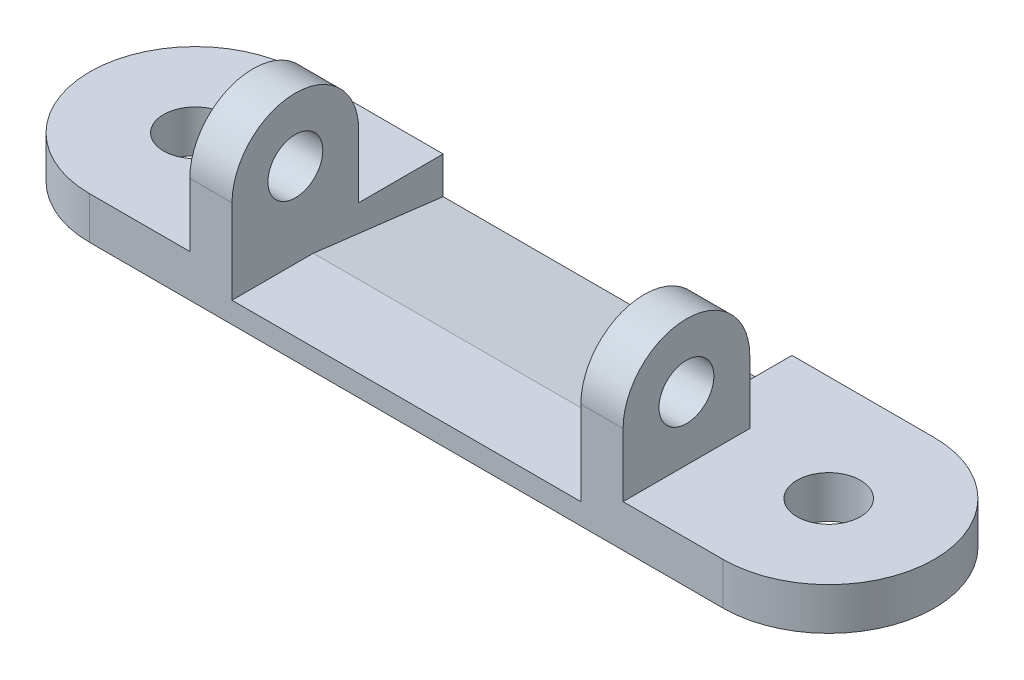
SolidWorks part; units mm, degrees
ref_plane "Front Plane" through (0, 0, 0) normal (0, 0, 1) x (1, 0, 0)
ref_plane "Top Plane" through (0, 0, 0) normal (0, 1, 0) x (1, 0, 0)
ref_plane "Right Plane" through (0, 0, 0) normal (1, 0, 0) x (0, 0, -1)
sketch "Sketch1" plane through (0, 0, 0) normal (0, 1, 0) x (1, 0, 0)
  line L1 (-30, 10) -> (30, 10)
  line L2 (-30, 10) -> (-30, -10) construction
  line L3 (-30, -10) -> (30, -10)
  line L4 (30, 10) -> (30, -10) construction
  line L5 (-30, 10) -> (30, -10) construction
  line L6 (-30, -10) -> (30, 10) construction
  arc A0 (-30, 10) -> (-30, -10) centre (-30, 0) ccw
  arc A1 (30, 10) -> (30, -10) centre (30, 0) cw
  point P0 (0, 0)
  dimension "D1" = 60
  dimension "D2" = 20
extrude "Boss-Extrude1" add sketch "Sketch1" along normal blind 4
sketch "Sketch2" plane through (0, 4, 0) normal (0, 1, 0) x (1, 0, 0)
  circle A0 centre (-30, 0) radius 3
  circle A1 centre (30, 0) radius 3
  arc A2 (-30, 10) -> (-30, -10) centre (-30, 0) ccw construction
  arc A3 (30, -10) -> (30, 10) centre (30, 0) ccw construction
  dimension "D1" = 6
extrude "Cut-Extrude1" cut sketch "Sketch2" against normal through all
sketch3d "3DSketch1"
  line L0 (-16.5227, 4, 10) -> (-16.5227, 4, -2)
  line L1 (-30, 4, 10) -> (30, 4, 10) construction
  line L4 (-16.5227, 4, 10) -> (-16.5227, 10, 10)
  line L5 (-16.5227, 4, -2) -> (-16.5227, 10, -2)
  arc A0 (-16.5227, 10, 10) -> (-16.5227, 10, -2) centre (-16.5227, 10, 4) cw
  point P11 (-22.5227, 10, 4)
  dimension "D1" = 17
  dimension "D2" = 6
  dimension "D3" = 12
extrude "Boss-Extrude2" add sketch "3DSketch1" along direction (1, 0, 0) on the side of the normal blind 4
sketch "Sketch3" plane through (-16.5227, 0, 0) normal (1, 0, 0) x (0, 0, -1)
  circle A0 centre (-4, 10) radius 2.6
  arc A1 (2, 10) -> (-10, 10) centre (-4, 10) ccw construction
  dimension "D1" = 5.2
extrude "Cut-Extrude2" cut sketch "Sketch3" against normal through all
sketch "Sketch4" plane through (0, 0, 0) normal (1, 0, 0) x (0, 0, -1)
  line L0 (-10, 2) -> (-2.3, 2)
  line L1 (-10, 4) -> (-10, 0) construction
  line L2 (-2.3, 2) -> (10, 0.5)
  line L3 (10, 4) -> (10, 0) construction
  line L4 (-10, 2) -> (-10, 0)
  line L5 (-10, 0) -> (10, 0)
  line L6 (10, 0) -> (10, 0.5)
  dimension "D1" = 0.5
  dimension "D2" = 2
  dimension "D3" = 7.7
extrude "Cut-Extrude3" cut sketch "Sketch4" against normal up to surface (16.5227 mm away) flip side to cut up to face at (-16.5227, 10, 1.4)
mirror "Mirror1" about plane through (0, 0, 0) normal (1, 0, 0) of "Cut-Extrude3", "Cut-Extrude2", "Boss-Extrude2"
